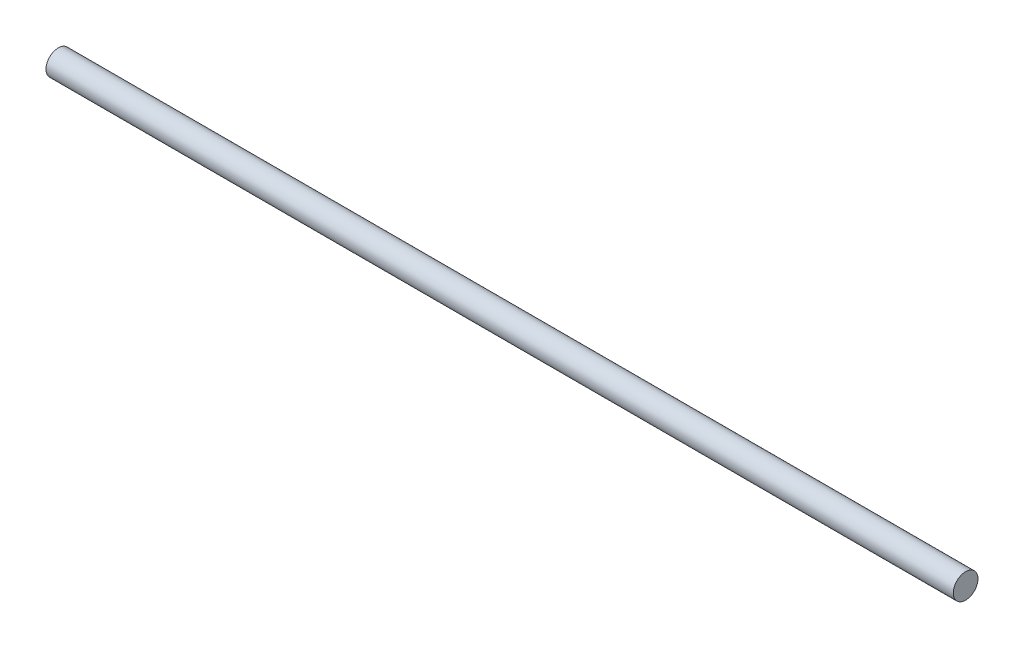
SolidWorks part; units mm, degrees
ref_plane "Top Plane" through (0, 0, 0) normal (0, 0, 1) x (1, 0, 0)
ref_plane "Right Plane" through (0, 0, 0) normal (0, 1, 0) x (1, 0, 0)
ref_plane "Front Plane" through (0, 0, 0) normal (1, 0, 0) x (0, 0, -1)
sketch "Sketch2" plane through (0, 0, 0) normal (1, 0, 0) x (0, 0, -1)
  circle A0 centre (0, 0) radius 1.5
  dimension "D1" = 3
extrude "Boss-Extrude1" add sketch "Sketch2" along normal blind 110
